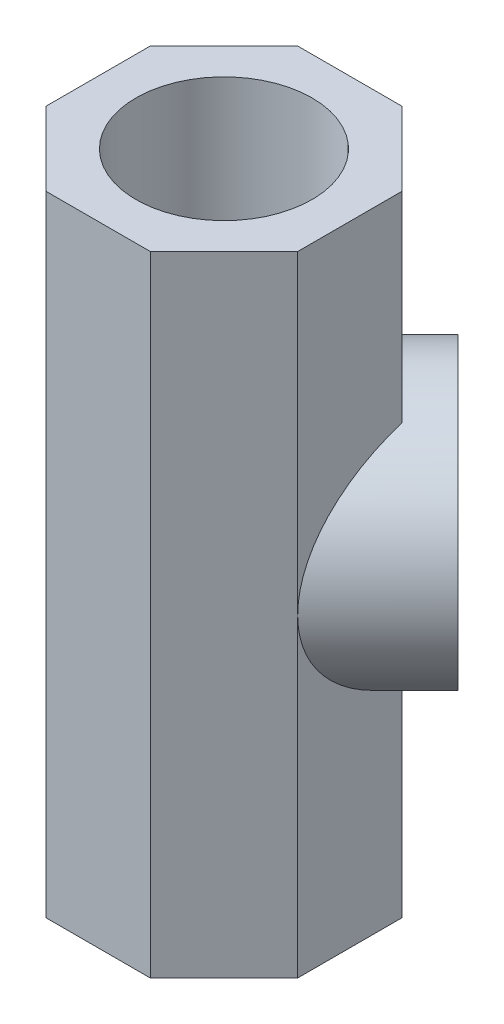
SolidWorks part; units mm, degrees
ref_plane "Front Plane" through (0, 0, 0) normal (0, 0, 1) x (1, 0, 0)
ref_plane "Top Plane" through (0, 0, 0) normal (0, 1, 0) x (1, 0, 0)
ref_plane "Right Plane" through (0, 0, 0) normal (1, 0, 0) x (0, 0, -1)
sketch "Sketch1" plane through (0, 0, 0) normal (0, 1, 0) x (1, 0, 0)
  line L1 (6.5756, -15.875) -> (15.875, -6.5756)
  line L2 (15.875, -6.5756) -> (15.875, 6.5756)
  line L3 (15.875, 6.5756) -> (6.5756, 15.875)
  line L4 (6.5756, 15.875) -> (-6.5756, 15.875)
  line L5 (-6.5756, 15.875) -> (-15.875, 6.5756)
  line L6 (-15.875, 6.5756) -> (-15.875, -6.5756)
  line L7 (-15.875, -6.5756) -> (-6.5756, -15.875)
  line L8 (-6.5756, -15.875) -> (6.5756, -15.875)
  circle A0 centre (0, 0) radius 15.875 construction
  circle A1 centre (0, 0) radius 11.1125
  dimension "D2" = 22.225
  dimension "D1" = 31.75
extrude "Boss-Extrude1" add sketch "Sketch1" along normal blind 79.375
ref_plane "Plane1" through (14.7609, 0, -14.7609) normal (0.7071, 0, -0.7071) x (-0.7071, 0, -0.7071)
sketch "Sketch2" plane through (14.7609, 0, -14.7609) normal (0.7071, 0, -0.7071) x (-0.7071, 0, -0.7071)
  line L0 (-6.5756, 39.6875) -> (0, 39.6347) construction
  line L1 (-6.5756, 79.375) -> (-6.5756, 0) construction
  line L2 (-15.875, 79.375) -> (-15.875, 0) construction
  circle A0 centre (0, 39.6347) radius 15.875
extrude "Boss-Extrude2" add sketch "Sketch2" against normal up to next
